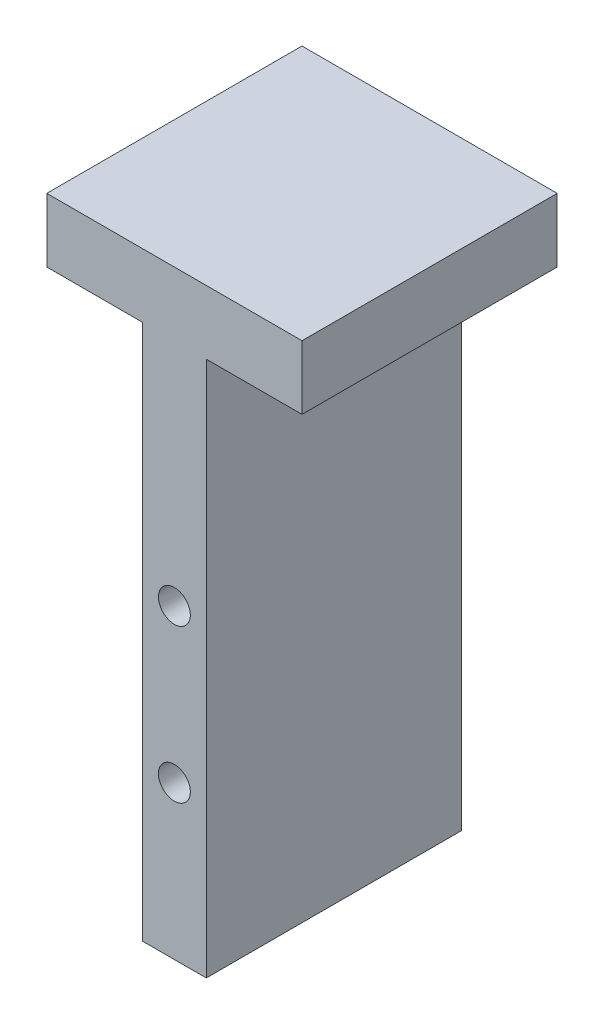
SolidWorks part; units mm, degrees
ref_plane "前基準面" through (0, 0, 0) normal (0, 0, 1) x (1, 0, 0)
ref_plane "上基準面" through (0, 0, 0) normal (0, 1, 0) x (1, 0, 0)
ref_plane "右基準面" through (0, 0, 0) normal (1, 0, 0) x (0, 0, -1)
sketch "草圖1" plane through (0, 0, 0) normal (0, 1, 0) x (1, 0, 0)
  line L1 (-10, -10) -> (10, -10)
  line L2 (-10, -10) -> (-10, 10)
  line L3 (-10, 10) -> (10, 10)
  line L4 (10, -10) -> (10, 10)
  line L5 (-10, -10) -> (10, 10) construction
  line L6 (-10, 10) -> (10, -10) construction
  point P0 (0, 0)
  dimension "D1" = 20
  dimension "D2" = 20
extrude "填料-伸長1" add sketch "草圖1" along normal blind 5
sketch "草圖2" plane through (0, 0, 0) normal (0, -1, 0) x (1, 0, 0)
  line L0 (-10, 10) -> (10, 10) construction
  line L1 (-2.5, -10) -> (2.5, -10)
  line L2 (-2.5, -10) -> (-2.5, 10)
  line L3 (-2.5, 10) -> (2.5, 10)
  line L4 (2.5, -10) -> (2.5, 10)
  line L5 (-2.5, -10) -> (2.5, 10) construction
  line L6 (-2.5, 10) -> (2.5, -10) construction
  point P0 (0, 0)
  dimension "D1" = 5
extrude "填料-伸長2" add sketch "草圖2" along normal blind 35
hole_wizard "M3 螺紋孔1" positions "草圖3" profile "草圖4" tap size "M3" standard "ISO"
sketch "草圖3" plane through (0, 0, 10) normal (0, 0, 1) x (1, 0, 0)
  line L0 (0, -35) -> (0, 5) construction
  line L1 (2.5, -35) -> (-2.5, -35) construction
  line L2 (-10, 5) -> (10, 5) construction
  point P0 (0, -18)
  point P2 (0, -30)
  dimension "D1" = 5
  dimension "D2" = 12
sketch "草圖4" plane through (0, -18, 10) normal (1, 0, 0) x (0, -1, 0)
  line L0 (0, 0) -> (0, 7.2511)
  line L1 (0, 7.2511) -> (1.25, 6.5)
  line L2 (1.25, 6.5) -> (1.25, 0)
  line L5 (1.25, 0) -> (0, 0)
  line L10 (0, 7.2511) -> (-1.25, 6.5) construction
  line L11 (0, -6.35) -> (0, 107.95) construction
  dimension "螺孔鑽直徑" = 2.5
  dimension "螺孔鑽深度" = 6.5
  dimension "導頭角度" = 118
cosmetic thread "鑽孔螺紋1" parameters "D1"=6, "D2"=3
cosmetic thread "鑽孔螺紋2" parameters "D1"=6, "D2"=3
mirror "鏡射1" about plane through (0, 0, 0) normal (0, 0, 1) of "M3 螺紋孔1"
sketch "草圖5" plane through (0, -35, 0) normal (0, -1, 0) x (1, 0, 0)
  line L0 (2.5, -10) -> (2.5, 10) construction
  line L1 (2.5, -10) -> (-2.5, -10)
  line L2 (2.5, -10) -> (2.5, 10)
  line L3 (2.5, 10) -> (-2.5, 10)
  line L4 (-2.5, -10) -> (-2.5, 10)
  line L5 (2.5, 0) -> (10, 0) construction
  line L6 (10, 10) -> (10, -10) construction
  line L7 (-2.5, 10) -> (-2.5, -10) construction
  dimension "D1" = 20
extrude "填料-伸長3" add sketch "草圖5" along normal blind 7
fillet "圓角1" [suppressed] radius 9
